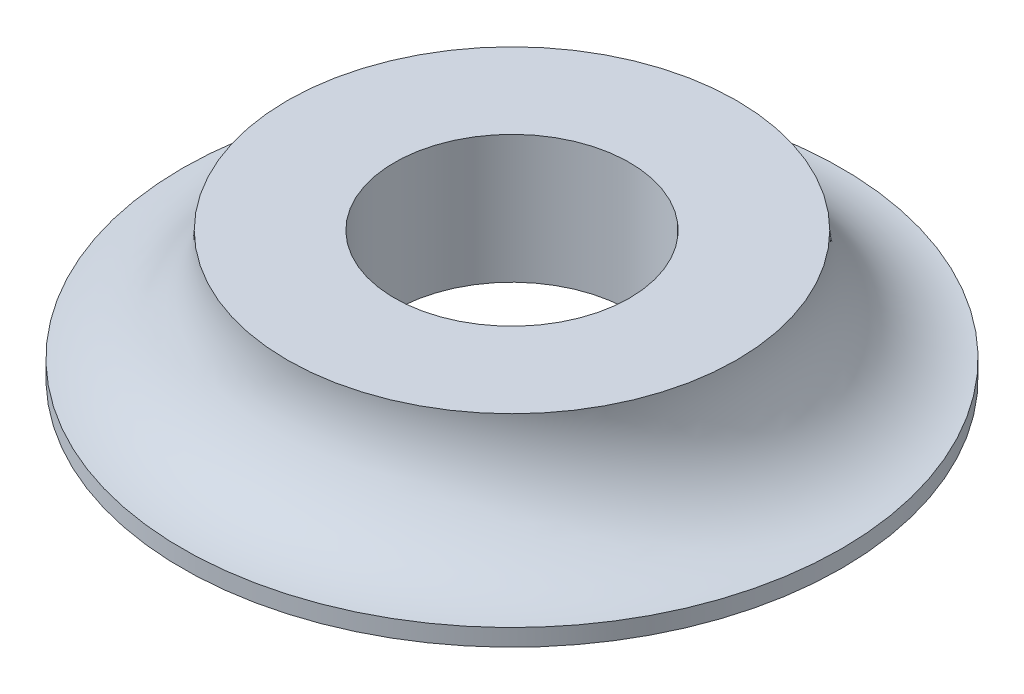
SolidWorks part; units mm, degrees
ref_plane "Front Plane" through (0, 0, 0) normal (0, 0, 1) x (1, 0, 0)
ref_plane "Top Plane" through (0, 0, 0) normal (0, 1, 0) x (1, 0, 0)
ref_plane "Right Plane" through (0, 0, 0) normal (1, 0, 0) x (0, 0, -1)
sketch "Sketch1" plane through (0, 0, 0) normal (0, 0, 1) x (1, 0, 0)
  line L0 (0, 0) -> (0, 4.318) construction
  line L1 (3.9624, 4.318) -> (3.9624, 0)
  line L3 (3.9624, 4.318) -> (7.5768, 4.318)
  line L4 (11.1125, 0) -> (11.1125, 0.5749)
  line L5 (3.9624, 0) -> (11.1125, 0)
  arc A0 (11.1125, 0.5749) -> (7.5768, 4.318) centre (11.2162, 4.2143) cw
  dimension "D1" = 3.9624
revolve "Revolve1" add sketch "Sketch1" angle 360 about L0
